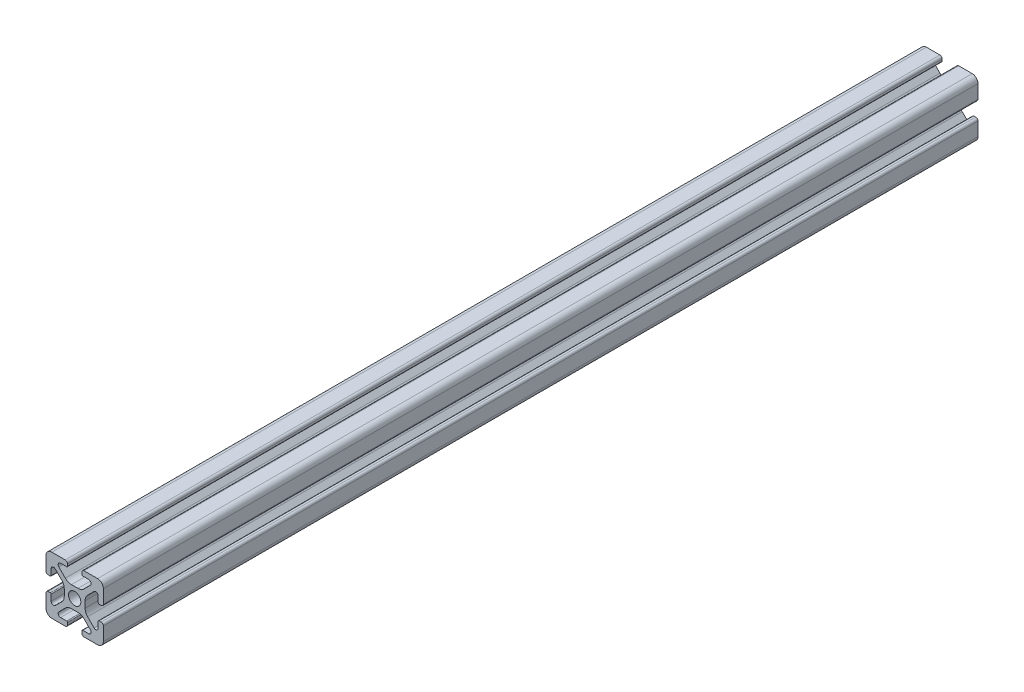
SolidWorks part; units mm, degrees
ref_plane "Front Plane" through (0, 0, 0) normal (0, 0, 1) x (1, 0, 0)
ref_plane "Top Plane" through (0, 0, 0) normal (0, 1, 0) x (1, 0, 0)
ref_plane "Right Plane" through (0, 0, 0) normal (1, 0, 0) x (0, 0, -1)
sketch "Sketch1" plane through (0, 0, 0) normal (0, 0, 1) x (1, 0, 0)
  line L2 (-9.9949, 7.9883) -> (-9.9949, 3.2893)
  line L3 (-7.9883, 9.9949) -> (-3.2893, 9.9949)
  line L4 (-2.5019, 9.2075) -> (-2.5019, 8.4963)
  line L5 (-2.8067, 8.1915) -> (-4.9149, 8.1915)
  line L6 (-5.5076, 6.7606) -> (-3.2528, 4.5058)
  line L7 (-6.7606, 5.5076) -> (-4.5058, 3.2528)
  line L8 (-8.1915, 4.9149) -> (-8.1915, 2.8067)
  line L9 (-8.4963, 2.5019) -> (-9.2075, 2.5019)
  line L11 (-1.1334, 3.6279) -> (1.1334, 3.6279)
  line L12 (-3.6279, 1.1334) -> (-3.6279, -1.1334)
  line L13 (8.4963, 2.5019) -> (9.2075, 2.5019)
  line L14 (8.1915, 4.9149) -> (8.1915, 2.8067)
  line L15 (9.9949, 7.9883) -> (9.9949, 3.2893)
  line L16 (7.9883, 9.9949) -> (3.2893, 9.9949)
  line L17 (2.5019, 9.2075) -> (2.5019, 8.4963)
  line L18 (2.8067, 8.1915) -> (4.9149, 8.1915)
  line L19 (3.6279, 1.1334) -> (3.6279, -1.1334)
  line L20 (5.5076, 6.7606) -> (3.2528, 4.5058)
  line L21 (6.7606, 5.5076) -> (4.5058, 3.2528)
  line L22 (-8.4963, -2.5019) -> (-9.2075, -2.5019)
  line L23 (-8.1915, -4.9149) -> (-8.1915, -2.8067)
  line L24 (-6.7606, -5.5076) -> (-4.5058, -3.2528)
  line L25 (-5.5076, -6.7606) -> (-3.2528, -4.5058)
  line L26 (-2.8067, -8.1915) -> (-4.9149, -8.1915)
  line L27 (-2.5019, -9.2075) -> (-2.5019, -8.4963)
  line L28 (-7.9883, -9.9949) -> (-3.2893, -9.9949)
  line L29 (-9.9949, -7.9883) -> (-9.9949, -3.2893)
  line L30 (9.9949, -7.9883) -> (9.9949, -3.2893)
  line L31 (7.9883, -9.9949) -> (3.2893, -9.9949)
  line L32 (2.5019, -9.2075) -> (2.5019, -8.4963)
  line L33 (2.8067, -8.1915) -> (4.9149, -8.1915)
  line L34 (5.5076, -6.7606) -> (3.2528, -4.5058)
  line L35 (6.7606, -5.5076) -> (4.5058, -3.2528)
  line L36 (8.1915, -4.9149) -> (8.1915, -2.8067)
  line L37 (8.4963, -2.5019) -> (9.2075, -2.5019)
  line L38 (-1.1334, -3.6279) -> (1.1334, -3.6279)
  circle A0 centre (0, 0) radius 2.1463
  arc A1 (-9.9949, 7.9883) -> (-7.9883, 9.9949) centre (-7.9883, 7.9883) cw
  arc A2 (-6.7606, 5.5076) -> (-8.1915, 4.9149) centre (-7.3533, 4.9149) ccw
  arc A3 (-4.9149, 8.1915) -> (-5.5076, 6.7606) centre (-4.9149, 7.3533) ccw
  arc A4 (-3.2893, 9.9949) -> (-2.5019, 9.2075) centre (-3.2893, 9.2075) cw
  arc A5 (-9.9949, 3.2893) -> (-9.2075, 2.5019) centre (-9.2075, 3.2893) ccw
  arc A6 (-8.1915, 2.8067) -> (-8.4963, 2.5019) centre (-8.4963, 2.8067) cw
  arc A7 (-2.5019, 8.4963) -> (-2.8067, 8.1915) centre (-2.8067, 8.4963) cw
  arc A8 (-1.1334, 3.6279) -> (-3.2528, 4.5058) centre (-1.1334, 6.6251) cw
  arc A9 (-3.6279, 1.1334) -> (-4.5058, 3.2528) centre (-6.6251, 1.1334) ccw
  arc A10 (8.1915, 2.8067) -> (8.4963, 2.5019) centre (8.4963, 2.8067) ccw
  arc A11 (9.9949, 3.2893) -> (9.2075, 2.5019) centre (9.2075, 3.2893) cw
  arc A12 (9.9949, 7.9883) -> (7.9883, 9.9949) centre (7.9883, 7.9883) ccw
  arc A13 (3.2893, 9.9949) -> (2.5019, 9.2075) centre (3.2893, 9.2075) ccw
  arc A14 (2.5019, 8.4963) -> (2.8067, 8.1915) centre (2.8067, 8.4963) ccw
  arc A15 (1.1334, 3.6279) -> (3.2528, 4.5058) centre (1.1334, 6.6251) ccw
  arc A16 (3.6279, 1.1334) -> (4.5058, 3.2528) centre (6.6251, 1.1334) cw
  arc A17 (6.7606, 5.5076) -> (8.1915, 4.9149) centre (7.3533, 4.9149) cw
  arc A18 (4.9149, 8.1915) -> (5.5076, 6.7606) centre (4.9149, 7.3533) cw
  arc A19 (-3.6279, -1.1334) -> (-4.5058, -3.2528) centre (-6.6251, -1.1334) cw
  arc A20 (-1.1334, -3.6279) -> (-3.2528, -4.5058) centre (-1.1334, -6.6251) ccw
  arc A21 (-2.5019, -8.4963) -> (-2.8067, -8.1915) centre (-2.8067, -8.4963) ccw
  arc A22 (-8.1915, -2.8067) -> (-8.4963, -2.5019) centre (-8.4963, -2.8067) ccw
  arc A23 (-9.9949, -3.2893) -> (-9.2075, -2.5019) centre (-9.2075, -3.2893) cw
  arc A24 (-3.2893, -9.9949) -> (-2.5019, -9.2075) centre (-3.2893, -9.2075) ccw
  arc A25 (-4.9149, -8.1915) -> (-5.5076, -6.7606) centre (-4.9149, -7.3533) cw
  arc A26 (-6.7606, -5.5076) -> (-8.1915, -4.9149) centre (-7.3533, -4.9149) cw
  arc A27 (-9.9949, -7.9883) -> (-7.9883, -9.9949) centre (-7.9883, -7.9883) ccw
  arc A28 (9.9949, -7.9883) -> (7.9883, -9.9949) centre (7.9883, -7.9883) cw
  arc A29 (6.7606, -5.5076) -> (8.1915, -4.9149) centre (7.3533, -4.9149) ccw
  arc A30 (4.9149, -8.1915) -> (5.5076, -6.7606) centre (4.9149, -7.3533) ccw
  arc A31 (3.2893, -9.9949) -> (2.5019, -9.2075) centre (3.2893, -9.2075) cw
  arc A32 (9.9949, -3.2893) -> (9.2075, -2.5019) centre (9.2075, -3.2893) ccw
  arc A33 (8.1915, -2.8067) -> (8.4963, -2.5019) centre (8.4963, -2.8067) cw
  arc A34 (2.5019, -8.4963) -> (2.8067, -8.1915) centre (2.8067, -8.4963) cw
  arc A35 (1.1334, -3.6279) -> (3.2528, -4.5058) centre (1.1334, -6.6251) cw
  arc A36 (3.6279, -1.1334) -> (4.5058, -3.2528) centre (6.6251, -1.1334) ccw
extrude "Boss-Extrude1" add sketch "Sketch1" along normal mid plane 304.8
